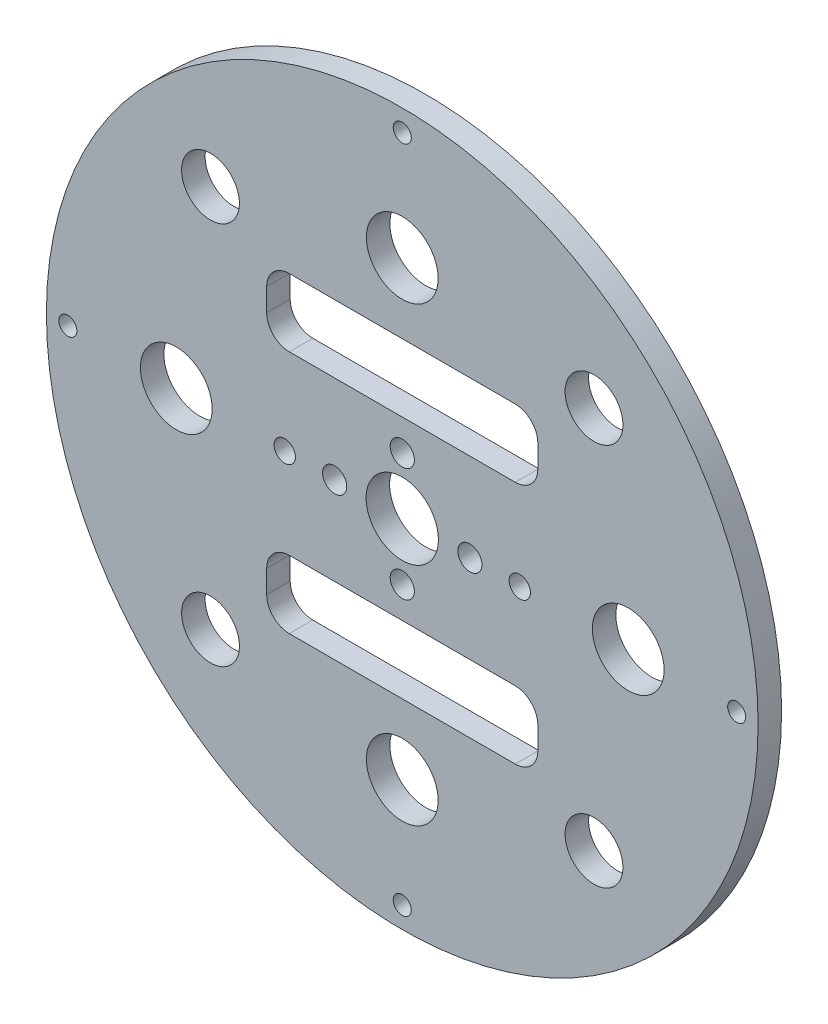
SolidWorks part; units mm, degrees
ref_plane "前视基准面" through (0, 0, 0) normal (0, 0, 1) x (1, 0, 0)
ref_plane "上视基准面" through (0, 0, 0) normal (0, 1, 0) x (1, 0, 0)
ref_plane "右视基准面" through (0, 0, 0) normal (1, 0, 0) x (0, 0, -1)
sketch "草图1" plane through (0, 0, 0) normal (0, 0, 1) x (1, 0, 0)
  circle A0 centre (0, 0) radius 50
  dimension "D1" = 100
extrude "凸台-拉伸1" add sketch "草图1" along normal blind 3.302
sketch "草图2" plane through (0, 0, 3.302) normal (0, 0, 1) x (1, 0, 0)
  line L0 (0, 0) -> (0, 69.5531) construction
  line L1 (0, 0) -> (-26.9408, 26.9408) construction
  line L2 (0, 0) -> (-38.1, 0) construction
  line L3 (0, 0) -> (-26.9408, -26.9408) construction
  circle A0 centre (-26.9408, 26.9408) radius 4.064
  circle A1 centre (-26.9408, -26.9408) radius 4.064
  circle A2 centre (26.9408, -26.9408) radius 4.064
  circle A3 centre (26.9408, 26.9408) radius 4.064
  circle A4 centre (0, 0) radius 38.1 construction
  dimension "D1" = 8.128
  dimension "D2" = 8.128
  dimension "D3" = 45
  dimension "D4" = 8.128
  dimension "D5" = 45
  dimension "D6" = 76.2
extrude "切除-拉伸1" cut sketch "草图2" against normal through all
sketch "草图4" plane through (0, 0, 3.302) normal (0, 0, 1) x (1, 0, 0)
  circle A0 centre (0, 0) radius 5.08
  dimension "D1" = 10.16
extrude "切除-拉伸3" cut sketch "草图4" against normal through all
sketch "草图7" plane through (0, 0, 3.302) normal (0, 0, 1) x (1, 0, 0)
  circle A0 centre (0, 46.99) radius 1.27
  circle A1 centre (46.99, 0) radius 1.27
  circle A2 centre (0, -46.99) radius 1.27
  circle A3 centre (-46.99, 0) radius 1.27
  point P12 (0, 0)
  dimension "D1" = 2.54
  dimension "D2" = 46.99
  dimension "D3" = 4
extrude "切除-拉伸6" cut sketch "草图7" against normal through all
hole_wizard "M3 Clearance Hole1" positions "Sketch1" profile "Sketch2" hole size "M3" standard "ANSI Metric"
sketch "Sketch1" plane through (0, 0, 3.302) normal (0, 0, 1) x (1, 0, 0)
  line L0 (0, 8) -> (0, 0) construction
  line L2 (0, 0) -> (0, 9.5) construction
  line L3 (0, 0) -> (-9.5, 0) construction
  circle A0 centre (0, 0) radius 8 construction
  circle A1 centre (0, 0) radius 9.5 construction
  point P4 (0, 8)
  point P27 (-9.5, 0)
  dimension "D1" = 19
  dimension "D2" = 16
  dimension "D3" = 0
  dimension "D4" = 90
sketch "Sketch2" plane through (0, 8, 3.302) normal (1, 0, 0) x (0, -1, 0)
  line L0 (0, 0) -> (0, 26.4215)
  line L1 (0, 26.4215) -> (1.7, 25.4)
  line L2 (1.7, 25.4) -> (1.7, 0)
  line L5 (1.7, 0) -> (0, 0)
  line L10 (0, 26.4215) -> (-1.7, 25.4) construction
  line L11 (0, -6.35) -> (0, 107.95) construction
  dimension "Hole Dia." = 3.4
  dimension "Hole Depth" = 25.4
  dimension "Drill Angle" = 118
hole_wizard "3/8 Clearance Hole1" positions "Sketch7" profile "Sketch8" hole size "3/8" standard "ANSI Inch" end condition through all
sketch "Sketch7" plane through (0, 0, 3.302) normal (0, 0, 1) x (1, 0, 0)
  circle A0 centre (0, 0) radius 31.75 construction
  point P0 (0, 31.75)
  point P2 (-31.75, 0)
  point P4 (31.75, 0)
  point P6 (0, -31.75)
  dimension "D1" = 63.5
sketch "Sketch8" plane through (0, 31.75, 3.302) normal (1, 0, 0) x (0, -1, 0)
  line L0 (0, 0) -> (0, 3.302)
  line L1 (0, 3.302) -> (5.0419, 3.302)
  line L2 (5.0419, 3.302) -> (5.0419, 0)
  line L5 (5.0419, 0) -> (0, 0)
  line L11 (0, -6.35) -> (0, 107.95) construction
  dimension "Thru Hole Dia." = 10.0838
  dimension "Thru Hole Depth" = 3.302
sketch "Sketch11" plane through (0, 0, 3.302) normal (0, 0, 1) x (1, 0, 0)
  line L0 (0, 0) -> (-11.8931, 0) construction
  line L1 (-16.51, 0) -> (0, 0) construction
  circle A0 centre (-16.51, 0) radius 1.5
  dimension "D1" = 16.51
  dimension "D2" = 3
  dimension "D3" = 0
extrude "Cut-Extrude5" cut sketch "Sketch11" against normal through all
pattern_circular "CirPattern1" count 2 over 360 about axis through (0, 0, 0) along (0, 0, 1) of "Cut-Extrude5"
pattern_circular "CirPattern2" count 2 over 360 about axis through (0, 0, 0) along (0, 0, 1) of "M3 Clearance Hole1"
sketch "Sketch12" plane through (0, 0, 3.302) normal (0, 0, 1) x (1, 0, 0)
  line L1 (-19.05, 21.9075) -> (19.05, 21.9075)
  line L2 (-19.05, 21.9075) -> (-19.05, 12.3825)
  line L3 (-19.05, 12.3825) -> (19.05, 12.3825)
  line L4 (19.05, 21.9075) -> (19.05, 12.3825)
  line L5 (-19.05, 21.9075) -> (19.05, 12.3825) construction
  line L6 (-19.05, 12.3825) -> (19.05, 21.9075) construction
  point P0 (0, 17.145)
  dimension "D1" = 17.145
  dimension "D2" = 38.1
  dimension "D3" = 9.525
extrude "Cut-Extrude6" cut sketch "Sketch12" against normal through all
fillet "Fillet1" radius 3.175 4 edges at (19.05, 21.9075, 1.651) (19.05, 12.3825, 1.651) (-19.05, 12.3825, 1.651) (-19.05, 21.9075, 1.651)
mirror "Mirror1" about plane through (0, 0, 0) normal (0, 1, 0) of "Fillet1", "Cut-Extrude6"
